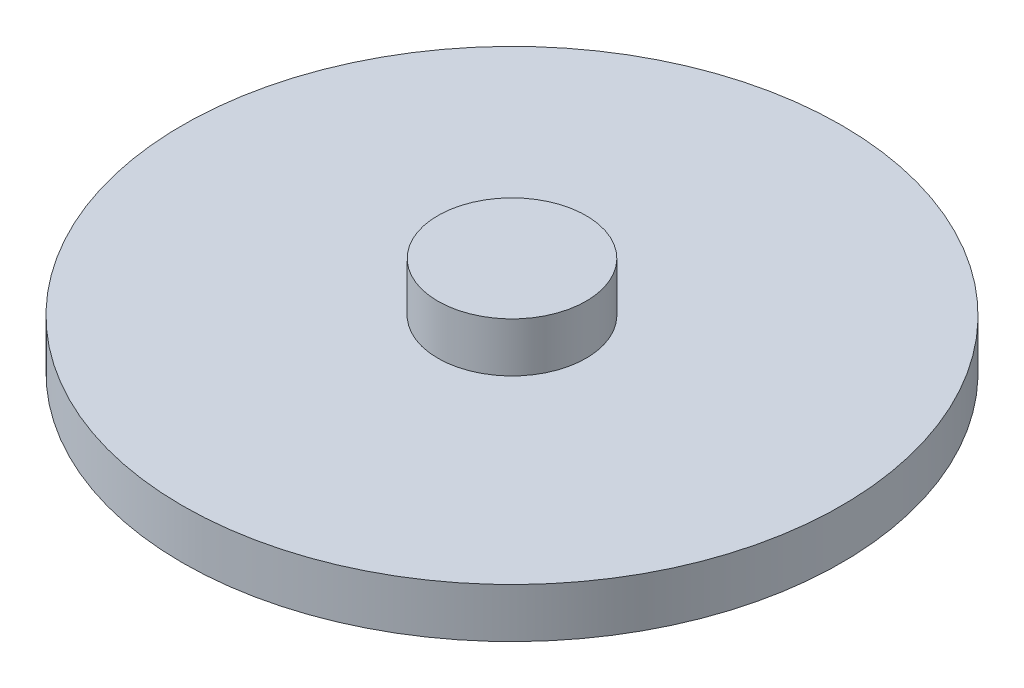
SolidWorks part; units mm, degrees
ref_plane "Front Plane" through (0, 0, 0) normal (0, 0, 1) x (1, 0, 0)
ref_plane "Top Plane" through (0, 0, 0) normal (0, 1, 0) x (1, 0, 0)
ref_plane "Right Plane" through (0, 0, 0) normal (1, 0, 0) x (0, 0, -1)
sketch "Sketch1" plane through (0, 0, 0) normal (0, 1, 0) x (1, 0, 0)
  circle A0 centre (-10.2691, 11.384) radius 20
  dimension "D1" = 40
extrude "Boss-Extrude1" add sketch "Sketch1" along normal blind 3
sketch "Sketch2" plane through (0, 3, 0) normal (0, 1, 0) x (1, 0, 0)
  circle A0 centre (-10.2691, 11.384) radius 4.5
  dimension "D1" = 9
extrude "Boss-Extrude2" add sketch "Sketch2" along normal blind 3
